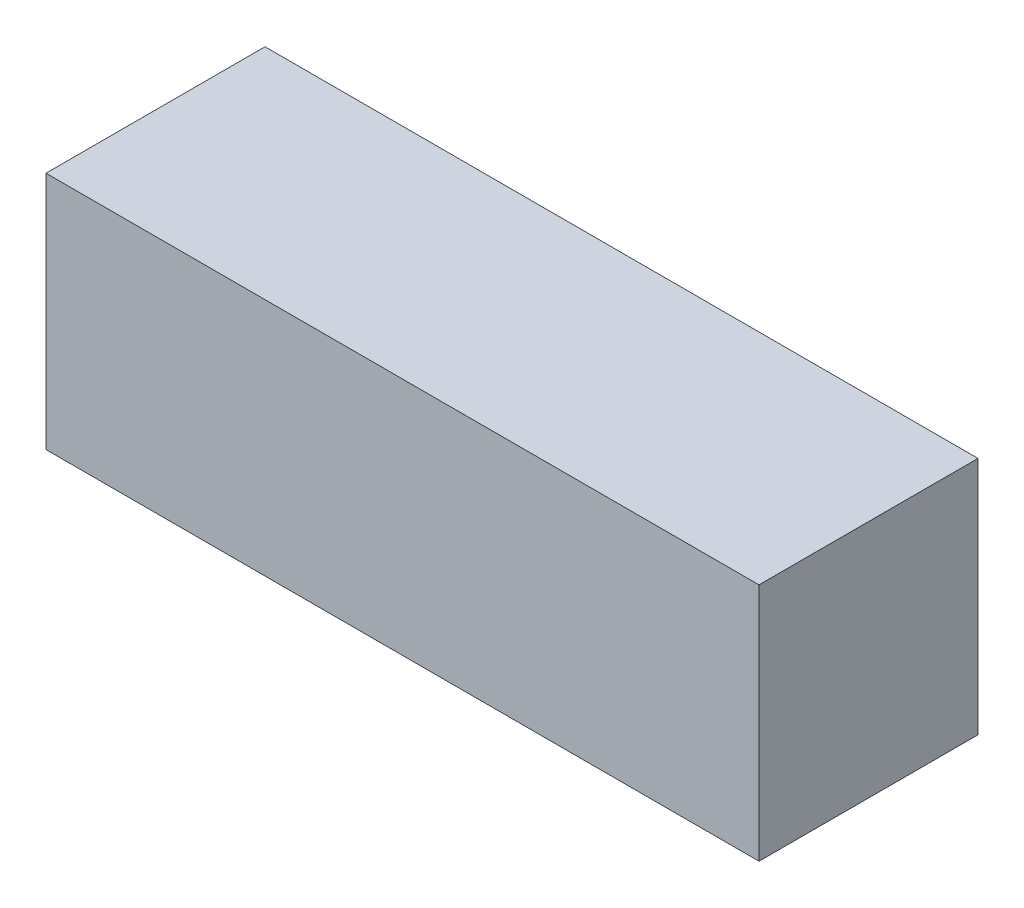
SolidWorks part; units mm, degrees
ref_plane "Front Plane" through (0, 0, 0) normal (0, 0, 1) x (1, 0, 0)
ref_plane "Top Plane" through (0, 0, 0) normal (0, 1, 0) x (1, 0, 0)
ref_plane "Right Plane" through (0, 0, 0) normal (1, 0, 0) x (0, 0, -1)
sketch "Sketch1" plane through (0, 0, 0) normal (0, 0, 1) x (1, 0, 0)
  line L1 (-70, -23.5) -> (70, -23.5)
  line L2 (-70, -23.5) -> (-70, 23.5)
  line L3 (-70, 23.5) -> (70, 23.5)
  line L4 (70, -23.5) -> (70, 23.5)
  line L5 (-70, -23.5) -> (70, 23.5) construction
  line L6 (-70, 23.5) -> (70, -23.5) construction
  point P0 (0, 0)
  dimension "D1" = 140
  dimension "D2" = 47
extrude "Boss-Extrude1" add sketch "Sketch1" along normal blind 43
